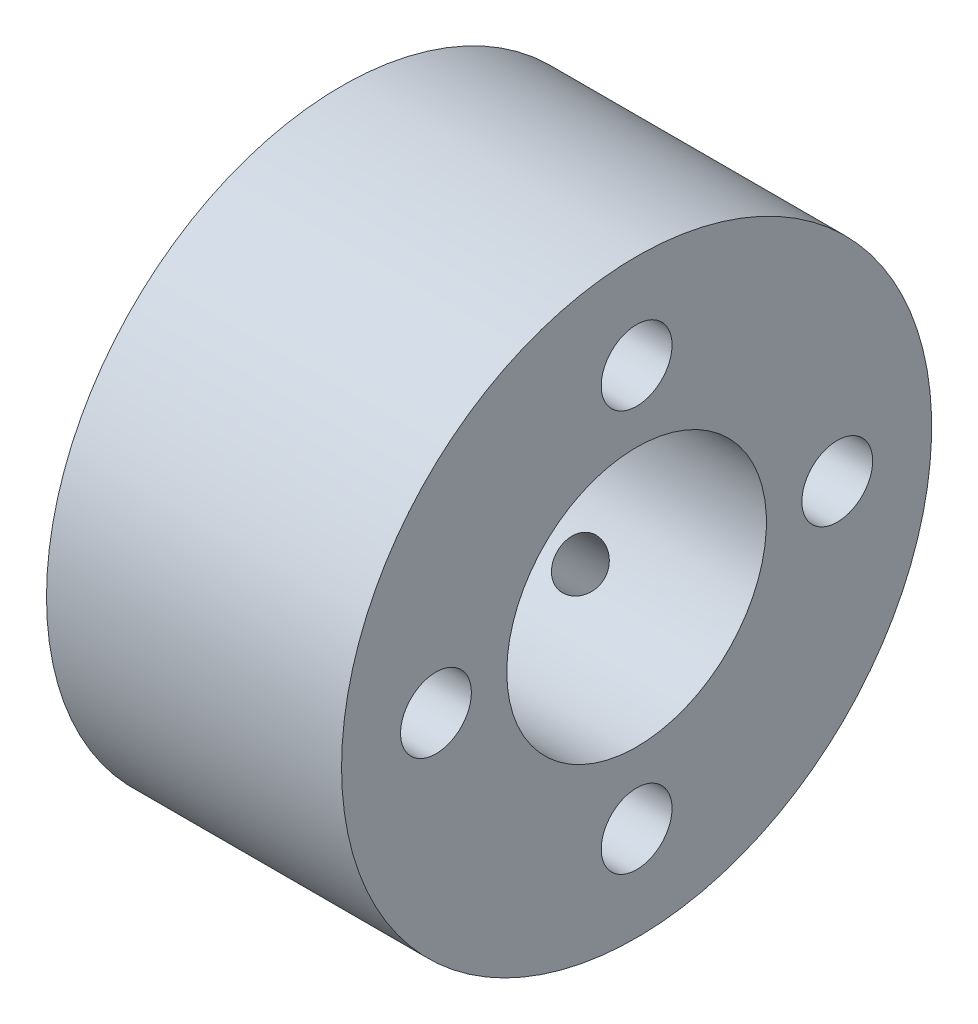
SolidWorks part; units mm, degrees
material "Cast Alloy Steel"
ref_plane "Ön Düzlem" through (0, 0, 0) normal (0, 0, 1) x (1, 0, 0)
ref_plane "Üst Düzlem" through (0, 0, 0) normal (0, 1, 0) x (1, 0, 0)
ref_plane "Sağ Düzlem" through (0, 0, 0) normal (1, 0, 0) x (0, 0, -1)
sketch "Sketch1" plane through (0, 0, 0) normal (0, 1, 0) x (1, 0, 0)
  line L0 (-12.5, 11) -> (12.5, 11)
  line L1 (12.5, 11) -> (12.5, 25)
  line L2 (12.5, 25) -> (-12.5, 25)
  line L3 (-12.5, 25) -> (-12.5, 11)
  line L6 (-25.731, 0) -> (30.0605, 0) construction
  point P6 (0, 11)
  dimension "D3" = 25
  dimension "D4" = 14
  dimension "D5" = 11
revolve "Revolve2" add sketch "Sketch1" angle 360 about L6
sketch "Sketch2" plane through (12.5, 0, 0) normal (1, 0, 0) x (0, 0, -1)
  circle A0 centre (0, 0) radius 17 construction
  dimension "D1" = 34
hole_wizard "Ø6.0mm Dowel Hole1" positions "Sketch3" profile "Sketch4" hole size "Ø6.0" standard "ANSI Metric" end condition through all
sketch "Sketch3" plane through (12.5, 0, 0) normal (1, 0, 0) x (0, 0, -1)
  circle A0 centre (0, 0) radius 17 construction
  point P0 (0, 17)
sketch "Sketch4" plane through (12.5, 17, 0) normal (0, 1, 0) x (0, 0, -1)
  line L0 (0, 0) -> (0, 25)
  line L1 (0, 25) -> (3, 25)
  line L2 (3, 25) -> (3, 0)
  line L5 (3, 0) -> (0, 0)
  line L11 (0, -6.35) -> (0, 107.95) construction
  dimension "Thru Hole Dia." = 6
  dimension "Thru Hole Depth" = 25
pattern_circular "CirPattern1" count 4 over 360 about axis through (0, 0, 0) along (1, 0, 0) of "Ø6.0mm Dowel Hole1"
hole_wizard "Ø4.0mm Dowel Hole1" positions "3DSketch1" profile "Sketch11" hole size "Ø4.0" standard "ANSI Metric"
sketch3d "3DSketch1"
  point P3 (0, -17.6776, -17.6778)
sketch "Sketch11" plane through (0, -17.6776, -17.6778) normal (1, 0, 0) x (0, 0.7071, -0.7071)
  line L0 (0, 0) -> (0, 14)
  line L1 (0, 14) -> (2, 14)
  line L2 (2, 14) -> (2, 0)
  line L5 (2, 0) -> (0, 0)
  line L11 (0, -6.35) -> (0, 107.95) construction
  dimension "Thru Hole Dia." = 4
  dimension "Thru Hole Depth" = 14
